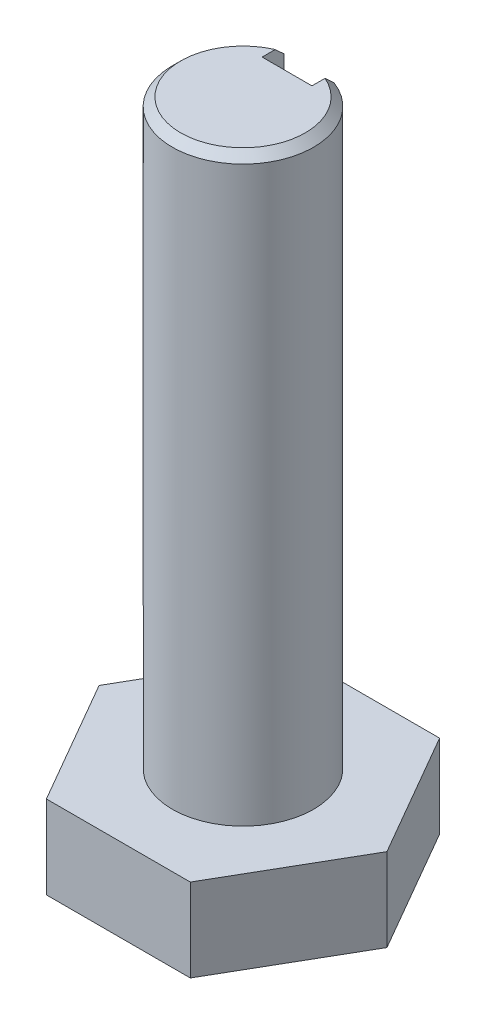
SolidWorks part; units mm, degrees
ref_plane "Front Plane" through (0, 0, 0) normal (0, 0, 1) x (1, 0, 0)
ref_plane "Top Plane" through (0, 0, 0) normal (0, 1, 0) x (1, 0, 0)
ref_plane "Right Plane" through (0, 0, 0) normal (1, 0, 0) x (0, 0, -1)
sketch "Sketch1" plane through (0, 0, 0) normal (0, 1, 0) x (1, 0, 0)
  line L0 (0, 15) -> (0, -15) construction
  line L1 (8.6603, 15) -> (-8.6603, 15)
  line L2 (-8.6603, 15) -> (-17.3205, 0)
  line L3 (-17.3205, 0) -> (-8.6603, -15)
  line L4 (-8.6603, -15) -> (8.6603, -15)
  line L5 (8.6603, -15) -> (17.3205, 0)
  line L6 (17.3205, 0) -> (8.6603, 15)
  line L7 (17.3205, 0) -> (-17.3205, 0) construction
  circle A0 centre (0, 0) radius 15 construction
  dimension "D1" = 30
extrude "Base Hexagonal 10mm" add sketch "Sketch1" along normal blind 10
sketch "Sketch2" plane through (0, 10, 0) normal (0, 1, 0) x (1, 0, 0)
  circle A0 centre (0, 0) radius 8.5
  dimension "D1" = 17
extrude "Eixo 70mm" add sketch "Sketch2" along normal blind 70
sketch "Sketch3" plane through (0, 80, 0) normal (0, 1, 0) x (1, 0, 0)
  line L0 (0, 0) -> (0, 8.5) construction
  line L2 (-3, 11.7) -> (3, 11.7)
  line L3 (-3, 11.7) -> (-3, 5.3)
  line L4 (-3, 5.3) -> (3, 5.3)
  line L5 (3, 11.7) -> (3, 5.3)
  line L6 (-3, 11.7) -> (3, 5.3) construction
  line L7 (-3, 5.3) -> (3, 11.7) construction
  circle A0 centre (0, 0) radius 8.5 construction
  dimension "D1" = 5.3
  dimension "D2" = 6
extrude "Rasgo de Chaveta" cut sketch "Sketch3" against normal blind 40
fillet "Raio 2mm" radius 2 2 edges at (-3, 40, -6.6265) (3, 40, -6.6265)
chamfer "Chanfro 1x45°" distance 1 angle 45 1 edges at (0, 80, 8.5)
